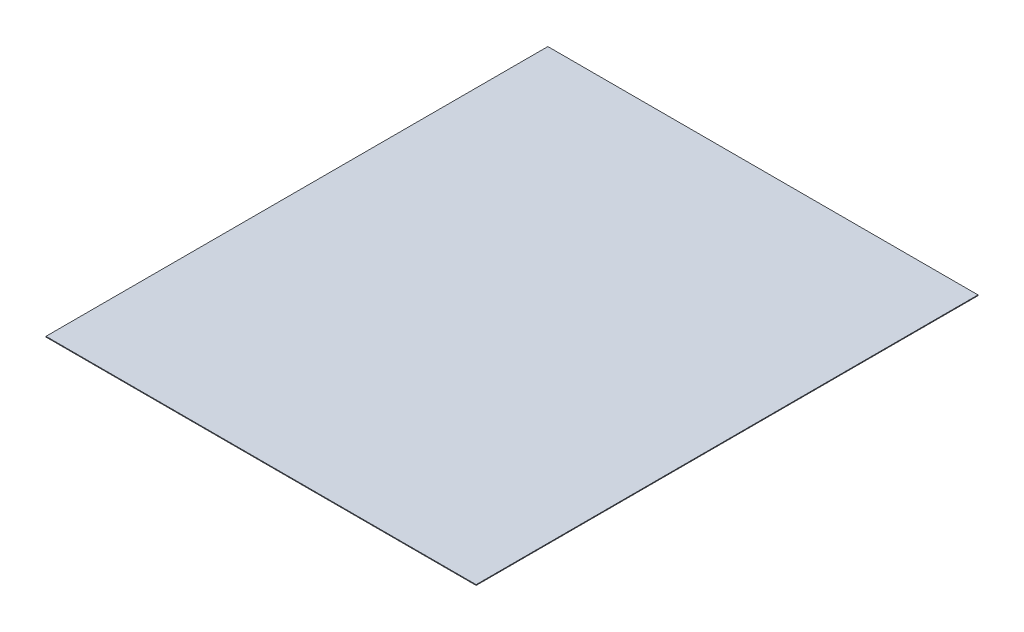
SolidWorks part; units mm, degrees
ref_plane "Alzado" through (0, 0, 0) normal (0, 0, 1) x (1, 0, 0)
ref_plane "Planta" through (0, 0, 0) normal (0, 1, 0) x (1, 0, 0)
ref_plane "Vista lateral" through (0, 0, 0) normal (1, 0, 0) x (0, 0, -1)
sketch "Croquis1" plane through (0, 0, 0) normal (0, 0, 1) x (1, 0, 0)
  line L1 (0, 0) -> (60000, 0)
  line L2 (0, 0) -> (0, 100)
  line L3 (0, 100) -> (60000, 100)
  line L4 (60000, 0) -> (60000, 100)
  dimension "D1" = 100
  dimension "D2" = 60000
extrude "Saliente-Extruir1" add sketch "Croquis1" against normal blind 70000
